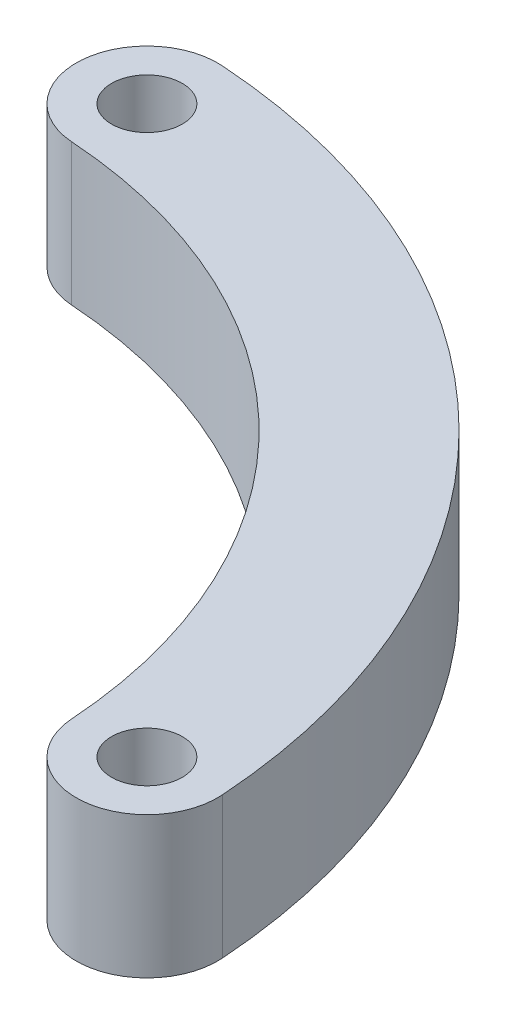
SolidWorks part; units mm, degrees
ref_plane "Front" through (0, 0, 0) normal (0, 0, 1) x (1, 0, 0)
ref_plane "Top" through (0, 0, 0) normal (0, 1, 0) x (1, 0, 0)
ref_plane "Right" through (0, 0, 0) normal (1, 0, 0) x (0, 0, -1)
sketch "Sketch1" plane through (0, 0, 0) normal (0, 1, 0) x (1, 0, 0)
  line L1 (-10, -10) -> (10, -10) construction
  line L2 (-10, -10) -> (-10, 10) construction
  line L3 (-10, 10) -> (10, 10) construction
  line L4 (10, -10) -> (10, 10) construction
  line L5 (-10, -10) -> (10, 10) construction
  line L6 (-10, 10) -> (10, -10) construction
  circle A0 centre (-10, 10) radius 1.25
  circle A1 centre (10, -10) radius 1.25
  circle A2 centre (-10, 10) radius 2.5 construction
  circle A3 centre (10, -10) radius 2.5 construction
  arc A4 (-10.1694, 7.5057) -> (7.5057, -10.1694) centre (-11.4575, -11.4575) cw
  arc A5 (-9.8306, 12.4943) -> (12.4943, -9.8306) centre (-11.4575, -11.4575) cw
  arc A6 (-9.8306, 12.4943) -> (-10.1694, 7.5057) centre (-10, 10) ccw
  arc A7 (7.5057, -10.1694) -> (12.4943, -9.8306) centre (10, -10) ccw
  point P0 (0, 0)
  dimension "D2" = 2.5
  dimension "D3" = 5
  dimension "D4" = 24.0069
  dimension "D1" = 20
extrude "Boss-Extrude1" add sketch "Sketch1" along normal blind 5
